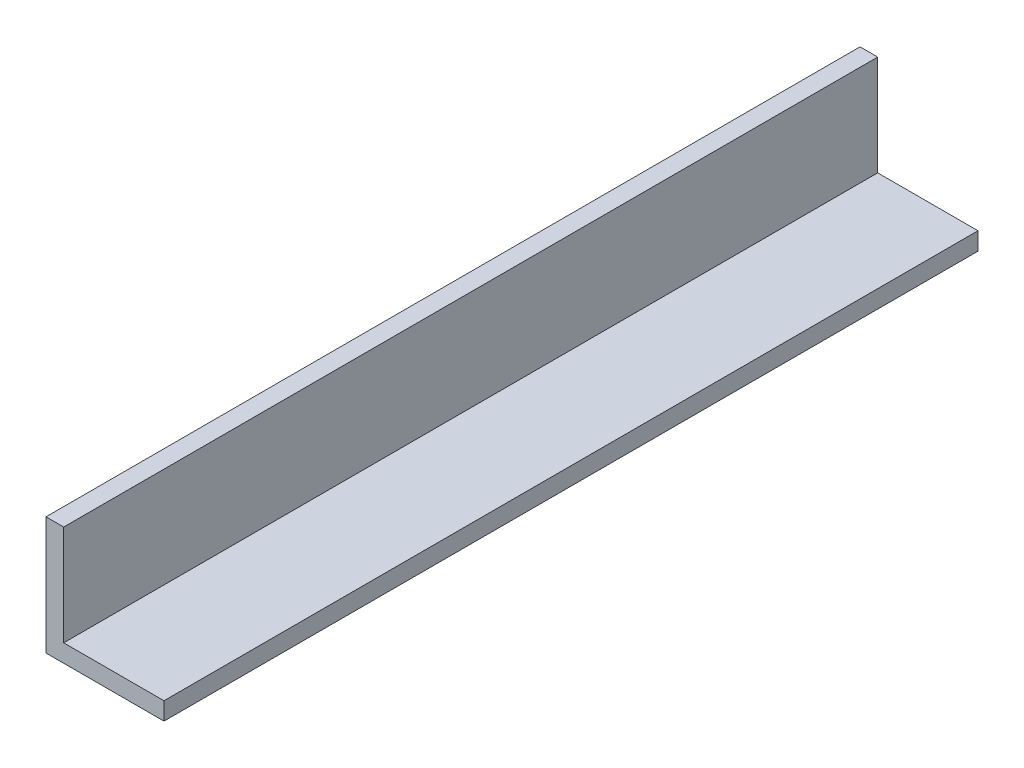
SolidWorks part; units mm, degrees
ref_plane "Front Plane" through (0, 0, 0) normal (0, 0, 1) x (1, 0, 0)
ref_plane "Top Plane" through (0, 0, 0) normal (0, 1, 0) x (1, 0, 0)
ref_plane "Right Plane" through (0, 0, 0) normal (1, 0, 0) x (0, 0, -1)
sketch "Sketch1" plane through (0, 0, 0) normal (0, 0, 1) x (1, 0, 0)
  line L0 (0, 0) -> (20, 0)
  line L1 (20, 0) -> (20, 3)
  line L2 (20, 3) -> (3, 3)
  line L3 (0, 0) -> (0, 20)
  line L4 (0, 20) -> (3, 20)
  line L5 (3, 20) -> (3, 3)
  dimension "D1" = 3
  dimension "D2" = 3
  dimension "D3" = 20
  dimension "D4" = 20
extrude "Boss-Extrude1" add sketch "Sketch1" along normal blind 138
